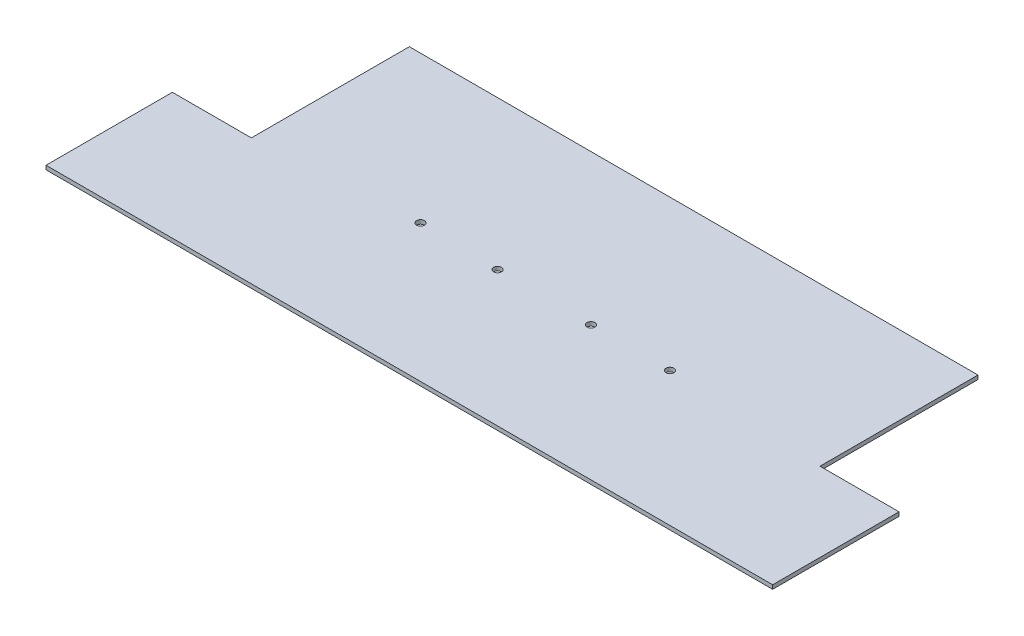
SolidWorks part; units mm, degrees
ref_plane "Front Plane" through (0, 0, 0) normal (0, 0, 1) x (1, 0, 0)
ref_plane "Top Plane" through (0, 0, 0) normal (0, 1, 0) x (1, 0, 0)
ref_plane "Right Plane" through (0, 0, 0) normal (1, 0, 0) x (0, 0, -1)
sketch "Sketch1" plane through (0, -25.4, 0) normal (0, -1, 0) x (1, 0, 0)
  line L0 (292.1, -317.5) -> (292.1, 317.5) construction
  line L1 (292.1, -114.3) -> (-292.1, -114.3)
  line L2 (292.1, -114.3) -> (292.1, -342.9)
  line L3 (292.1, -342.9) -> (-292.1, -342.9)
  line L4 (-292.1, -114.3) -> (-292.1, -342.9)
  line L5 (-292.1, -317.5) -> (-292.1, 317.5) construction
  line L6 (-355.6, -342.9) -> (355.6, -342.9) construction
  line L7 (292.1, -215.9) -> (228.6, -215.9)
  line L8 (228.6, -215.9) -> (228.6, -342.9)
  line L9 (0, -114.3) -> (0, -342.9) construction
  line L10 (-228.6, -215.9) -> (-228.6, -342.9)
  line L11 (-292.1, -215.9) -> (-228.6, -215.9)
  dimension "D1" = 228.6
  dimension "D2" = 63.5
  dimension "D3" = 127
extrude "Boss-Extrude1" add sketch "Sketch1" along normal blind 3.175 contours L1 L9 L3 L8 L7 L2 | L9 L1 L4 L11 L10 L3
sketch "Sketch2" plane through (0, -25.4, 0) normal (0, 1, 0) x (1, 0, 0)
  circle A0 centre (114.3, 152.4) radius 3.175 construction
  circle A1 centre (88.9, 127) radius 3.175 construction
  circle A2 centre (114.3, 152.4) radius 3.175
  circle A3 centre (88.9, 127) radius 3.175
  circle A6 centre (-76.2, 127) radius 3.175 construction
  circle A7 centre (-76.2, 127) radius 3.175
  circle A9 centre (-25.4, 127) radius 3.175 construction
  circle A10 centre (38.1, 127) radius 3.175 construction
  circle A12 centre (-101.6, 152.4) radius 3.175 construction
  circle A14 centre (-25.4, 127) radius 3.175
  circle A15 centre (38.1, 127) radius 3.175
  circle A17 centre (-101.6, 152.4) radius 3.175
  circle A18 centre (-101.6, 215.9) radius 3.175 construction
  circle A19 centre (114.3, 215.9) radius 3.175 construction
  circle A20 centre (-101.6, 215.9) radius 3.175
  circle A21 centre (114.3, 215.9) radius 3.175
  circle A22 centre (114.3, 279.4) radius 3.175 construction
  circle A23 centre (114.3, 279.4) radius 3.175
  circle A24 centre (-101.6, 279.4) radius 3.175 construction
  circle A25 centre (-101.6, 279.4) radius 3.175
hole_wizard "1/4 (0.25) Diameter Hole1" positions "Sketch3" profile "Sketch4" hole size "1/4" standard "ANSI Inch" end condition through all
sketch "Sketch3" plane through (0, -25.4, 0) normal (0, 1, 0) x (1, 0, 0)
  circle A2 centre (-37.9351, 223.1707) radius 3.175
  circle A3 centre (-37.9351, 223.1707) radius 3.175
  circle A6 centre (-101.4164, 224.7084) radius 3.175
  circle A7 centre (-101.4164, 224.7084) radius 3.175
  circle A10 centre (-98.8025, 332.6267) radius 3.175
  circle A11 centre (-98.8025, 332.6267) radius 3.175
  circle A14 centre (38.1, 222.25) radius 3.175
  circle A15 centre (38.1, 222.25) radius 3.175
  circle A18 centre (101.6, 222.25) radius 3.175
  circle A19 centre (101.6, 222.25) radius 3.175
  circle A22 centre (101.6, 330.2) radius 3.175
  circle A23 centre (101.6, 330.2) radius 3.175
  point P35 (-37.9351, 223.1707)
  point P42 (-101.4164, 224.7084)
  point P56 (38.1, 222.25)
  point P63 (101.6, 222.25)
  dimension "D1" = 0
  dimension "D2" = 0
  dimension "D3" = 0
  dimension "D4" = 0
  dimension "D5" = 0
  dimension "D6" = 0
sketch "Sketch4" plane through (-37.9351, -25.4, -223.1707) normal (1, 0, 0) x (0, 0, 1)
  line L0 (0, 0) -> (0, 3.175)
  line L1 (0, 3.175) -> (3.175, 3.175)
  line L2 (3.175, 3.175) -> (3.175, 0)
  line L5 (3.175, 0) -> (0, 0)
  line L11 (0, -6.35) -> (0, 107.95) construction
  dimension "Thru Hole Dia." = 6.35
  dimension "Thru Hole Depth" = 3.175
sketch "Sketch5" plane through (0, -25.4, 0) normal (0, 1, 0) x (1, 0, 0)
  line L0 (184.15, 152.4) -> (184.15, 304.8)
  line L1 (152.4, 152.4) -> (215.9, 152.4)
  line L2 (152.4, 152.4) -> (152.4, 304.8)
  line L3 (152.4, 304.8) -> (215.9, 304.8)
  line L4 (215.9, 152.4) -> (215.9, 304.8)
  line L5 (152.4, 228.6) -> (215.9, 228.6)
  arc A2 (215.9, 301.625) -> (212.725, 304.8) centre (215.9, 304.8) ccw
  arc A3 (152.4, 155.575) -> (155.575, 152.4) centre (152.4, 152.4) ccw
ref_plane "Plane1" through (184.15, 0, 0) normal (1, 0, 0) x (0, 0, -1)
ref_plane "Plane2" through (0, 0, -228.6) normal (0, 0, 1) x (1, 0, 0)
